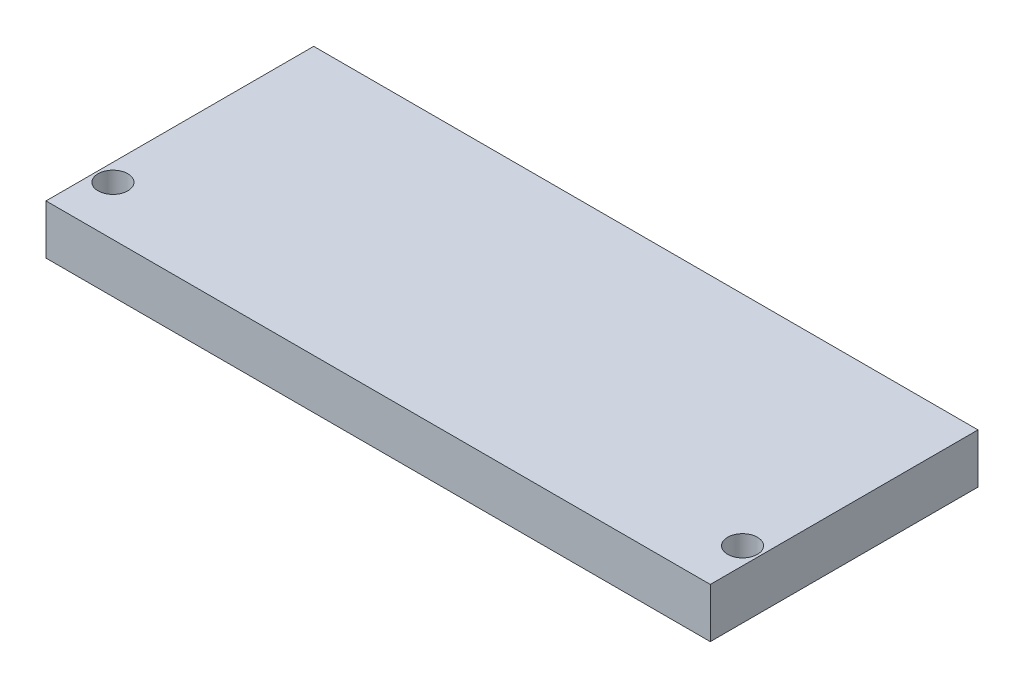
SolidWorks part; units mm, degrees
ref_plane "Front Plane" through (0, 0, 0) normal (0, 0, 1) x (1, 0, 0)
ref_plane "Top Plane" through (0, 0, 0) normal (0, 1, 0) x (1, 0, 0)
ref_plane "Right Plane" through (0, 0, 0) normal (1, 0, 0) x (0, 0, -1)
sketch "Sketch1" plane through (0, 0, 0) normal (0, 1, 0) x (1, 0, 0)
  line L0 (0, -55) -> (0, 55) construction
  line L1 (-33.5, -13.5) -> (33.5, -13.5)
  line L2 (-33.5, -13.5) -> (-33.5, 13.5)
  line L3 (-33.5, 13.5) -> (33.5, 13.5)
  line L4 (33.5, -13.5) -> (33.5, 13.5)
  line L5 (-33.5, -13.5) -> (33.5, 13.5) construction
  line L6 (-33.5, 13.5) -> (33.5, -13.5) construction
  circle A0 centre (-31.75, -8.5) radius 1.5
  circle A1 centre (31.75, -8.5) radius 1.5
  point P0 (0, 0)
  dimension "D3" = 3
  dimension "D4" = 1.75
  dimension "D5" = 5
  dimension "D6" = 63.5
  dimension "D1" = 67
  dimension "D2" = 27
extrude "Boss-Extrude1" add sketch "Sketch1" along normal blind 5
